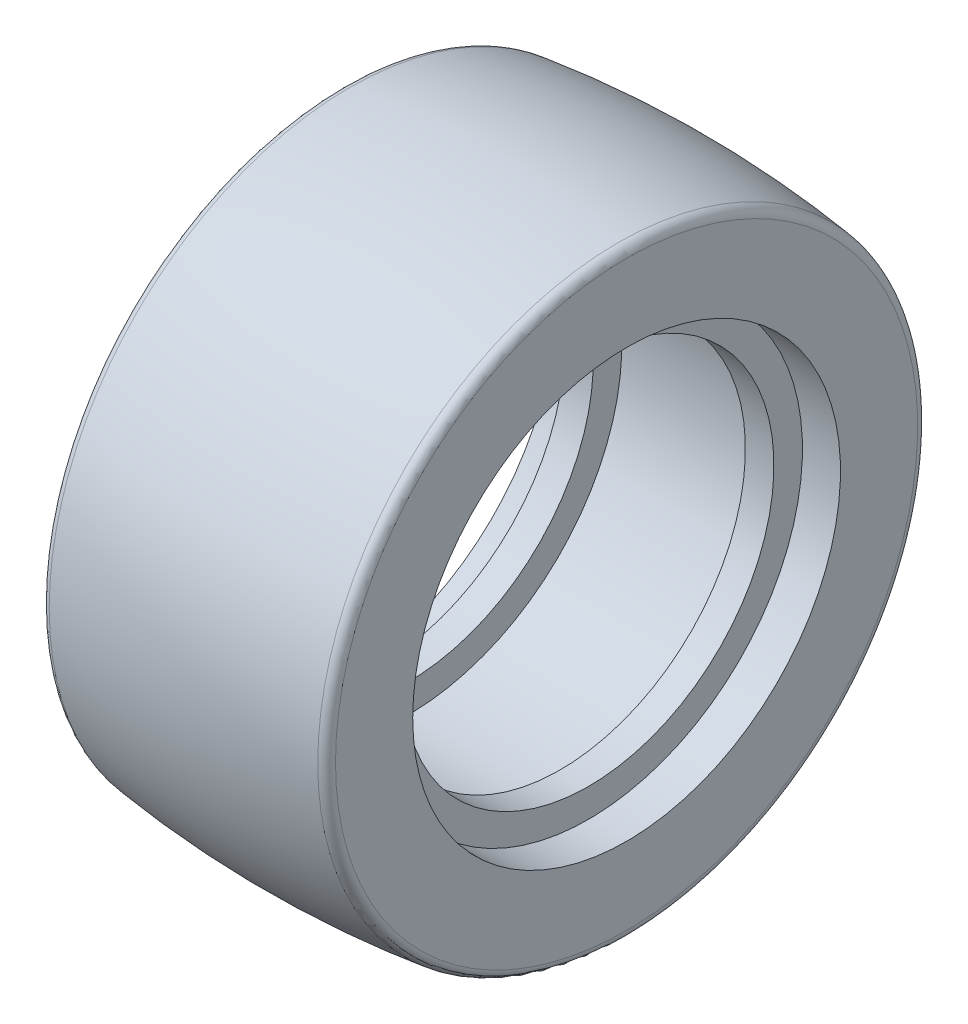
SolidWorks part; units mm, degrees
material "Силиконовая резина"
ref_plane "Спереди" through (0, 0, 0) normal (0, 0, 1) x (1, 0, 0)
ref_plane "Сверху" through (0, 0, 0) normal (0, 1, 0) x (1, 0, 0)
ref_plane "Справа" through (0, 0, 0) normal (1, 0, 0) x (0, 0, -1)
sketch "Эскиз1" plane through (0, 0, 0) normal (0, 0, 1) x (1, 0, 0)
  line L0 (-15, 22.5) -> (-11, 22.5)
  line L1 (-11, 22.5) -> (-11, 19.5)
  line L2 (-11, 19.5) -> (-8, 19.5)
  line L3 (-8, 19.5) -> (-8, 22.5)
  line L4 (-8, 22.5) -> (8, 22.5)
  line L5 (8, 22.5) -> (8, 19.5)
  line L6 (8, 19.5) -> (11, 19.5)
  line L7 (11, 19.5) -> (11, 22.5)
  line L8 (11, 22.5) -> (15, 22.5)
  line L9 (15, 22.5) -> (15, 31.5)
  line L10 (-15, 22.5) -> (-15, 31.5)
  line L11 (0, 29.5) -> (0, -2.8614) construction
  line L12 (-27.729, 0) -> (30.3752, 0) construction
  arc A0 (-15, 31.5) -> (15, 31.5) centre (0, -80.5) cw
  point P15 (0, 32.5)
  dimension "D1" = 4
  dimension "D2" = 3
  dimension "D3" = 3
  dimension "D4" = 30
  dimension "D5" = 9
  dimension "D7" = 45
  dimension "D6" = 10
  dimension "D8" = 65
revolve "Повернуть1" add sketch "Эскиз1" angle 360 about L12
fillet "Скругление1" radius 1 2 edges at (15, 0, 31.5) (-15, 0, 31.5)
equation "\"D6@Эскиз1\"=\"D5@Эскиз1\"+1"
